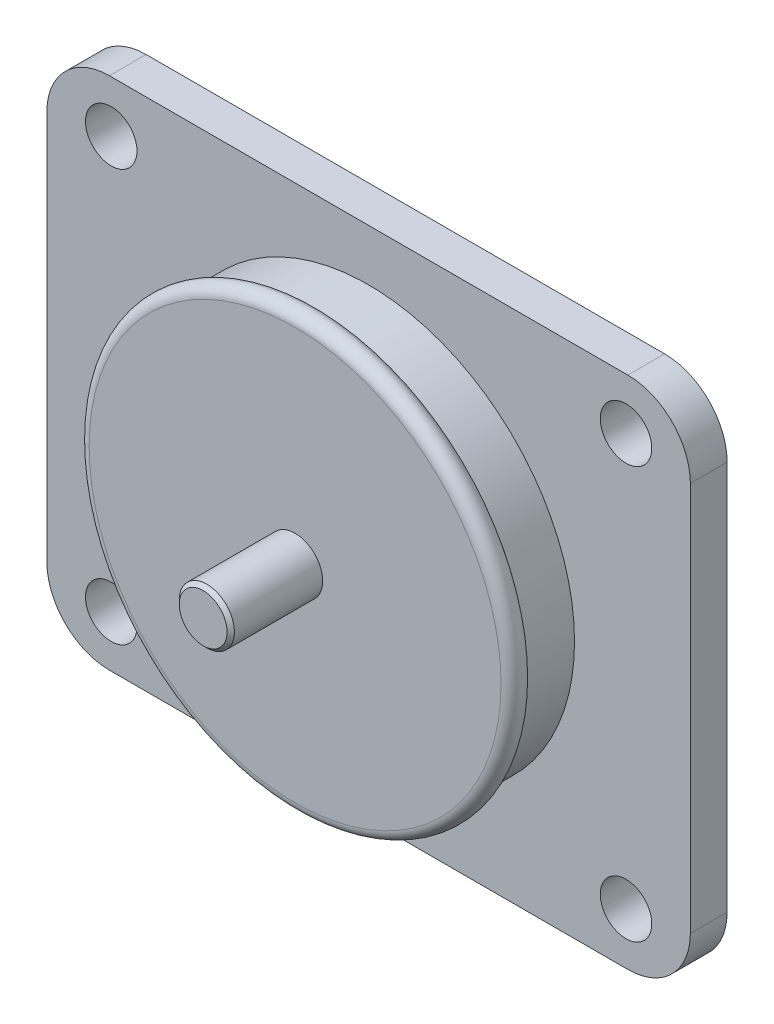
SolidWorks part; units mm, degrees
ref_plane "Front Plane" through (0, 0, 0) normal (0, 0, 1) x (1, 0, 0)
ref_plane "Top Plane" through (0, 0, 0) normal (0, 1, 0) x (1, 0, 0)
ref_plane "Right Plane" through (0, 0, 0) normal (1, 0, 0) x (0, 0, -1)
sketch "Sketch1" plane through (0, 0, 0) normal (0, 0, 1) x (1, 0, 0)
  line L1 (-70.5, 70) -> (70.5, 70)
  line L2 (-87.5, 53) -> (-87.5, -53)
  line L3 (-70.5, -70) -> (70.5, -70)
  line L4 (87.5, 53) -> (87.5, -53)
  line L5 (-87.5, 70) -> (87.5, -70) construction
  line L6 (-87.5, -70) -> (87.5, 70) construction
  arc A0 (70.5, -70) -> (87.5, -53) centre (70.5, -53) ccw
  arc A1 (-87.5, -53) -> (-70.5, -70) centre (-70.5, -53) ccw
  arc A2 (70.5, 70) -> (87.5, 53) centre (70.5, 53) cw
  arc A3 (-70.5, 70) -> (-87.5, 53) centre (-70.5, 53) ccw
  circle A4 centre (-70, 56) radius 7
  circle A5 centre (-70, -56) radius 7
  circle A6 centre (70, -56) radius 7
  circle A7 centre (70, 56) radius 7
  point P0 (0, 0)
  dimension "D3" = 17
  dimension "D4" = 14
  dimension "D1" = 175
  dimension "D2" = 140
  dimension "D5" = 112
extrude "Boss-Extrude1" add sketch "Sketch1" along normal blind 10
sketch "Sketch2" plane through (0, 0, 10) normal (0, 0, 1) x (1, 0, 0)
  circle A0 centre (0, 0) radius 56
  dimension "D1" = 112
extrude "Boss-Extrude2" add sketch "Sketch2" along normal blind 20
sketch "Sketch3" plane through (0, 0, 0) normal (0, 1, 0) x (1, 0, 0)
  line L0 (0, 0) -> (0, -42.1103) construction
  line L1 (-56, -10) -> (-56, -30) construction
  line L2 (-56, -30) -> (56, -30) construction
  circle A0 centre (-56, -27) radius 3
  dimension "D1" = 6
revolve "Revolve1" add sketch "Sketch3" angle 360 about L0
sketch "Sketch4" plane through (0, 0, 30) normal (0, 0, 1) x (1, 0, 0)
  circle A0 centre (0, 0) radius 7.5
  dimension "D1" = 15
extrude "Boss-Extrude3" add sketch "Sketch4" along normal blind 25
cosmetic thread "Cosmetic Thread1"
chamfer "Chamfer1" distance 1 angle 45 1 edges at (7.5, 0, 55)
sketch "Sketch5" plane through (0, 0, 0) normal (0, 0, -1) x (-1, 0, 0)
  circle A0 centre (0, 0) radius 45
  dimension "D1" = 90
extrude "Cut-Extrude1" cut sketch "Sketch5" against normal blind 2
scale "Scale1" scale about centroid uniform scaling yes scale factor 0.25
